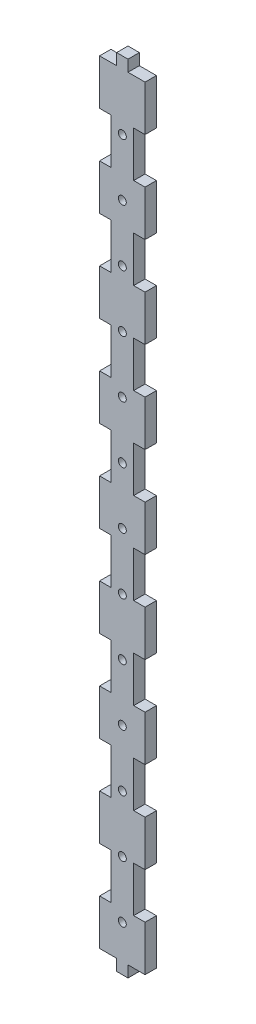
SolidWorks part; units mm, degrees
ref_plane "Front Plane" through (0, 0, 0) normal (0, 0, 1) x (1, 0, 0)
ref_plane "Top Plane" through (0, 0, 0) normal (0, 1, 0) x (1, 0, 0)
ref_plane "Right Plane" through (0, 0, 0) normal (1, 0, 0) x (0, 0, -1)
sketch "Model" plane through (0, 0, 0) normal (0, 0, 1) x (1, 0, 0)
  line L0 (5, -152.5) -> (0, -152.5)
  line L1 (5, -172.5) -> (5, -152.5)
  line L2 (-2.5, -172.5) -> (5, -172.5)
  line L3 (-2.5, -177.5) -> (-2.5, -172.5)
  line L4 (-7.5, -177.5) -> (-2.5, -177.5)
  line L5 (-7.5, -172.5) -> (-7.5, -177.5)
  line L6 (-15, -172.5) -> (-7.5, -172.5)
  line L7 (-15, -152.5) -> (-15, -172.5)
  line L8 (-10, -152.5) -> (-15, -152.5)
  line L9 (-10, -132.5) -> (-10, -152.5)
  line L10 (-15, -132.5) -> (-10, -132.5)
  line L11 (-15, -112.5) -> (-15, -132.5)
  line L12 (-10, -112.5) -> (-15, -112.5)
  line L13 (-10, -92.5) -> (-10, -112.5)
  line L14 (-15, -92.5) -> (-10, -92.5)
  line L15 (-15, -72.5) -> (-15, -92.5)
  line L16 (-10, -72.5) -> (-15, -72.5)
  line L17 (-10, -52.5) -> (-10, -72.5)
  line L18 (-15, -52.5) -> (-10, -52.5)
  line L19 (-15, -32.5) -> (-15, -52.5)
  line L20 (-10, -32.5) -> (-15, -32.5)
  line L21 (-10, -12.5) -> (-10, -32.5)
  line L22 (-15, -12.5) -> (-10, -12.5)
  line L23 (-15, 7.5) -> (-15, -12.5)
  line L24 (-10, 7.5) -> (-15, 7.5)
  line L25 (-10, 27.5) -> (-10, 7.5)
  line L26 (-15, 27.5) -> (-10, 27.5)
  line L27 (-15, 47.5) -> (-15, 27.5)
  line L28 (-10, 47.5) -> (-15, 47.5)
  line L29 (-10, 67.5) -> (-10, 47.5)
  line L30 (-15, 67.5) -> (-10, 67.5)
  line L31 (-15, 87.5) -> (-15, 67.5)
  line L32 (-10, 87.5) -> (-15, 87.5)
  line L33 (-10, 107.5) -> (-10, 87.5)
  line L34 (-15, 107.5) -> (-10, 107.5)
  line L35 (-15, 127.5) -> (-15, 107.5)
  line L36 (-10, 127.5) -> (-15, 127.5)
  line L37 (-10, 147.5) -> (-10, 127.5)
  line L38 (-15, 147.5) -> (-10, 147.5)
  line L39 (-15, 167.5) -> (-15, 147.5)
  line L40 (-7.5, 167.5) -> (-15, 167.5)
  line L41 (-7.5, 172.5) -> (-7.5, 167.5)
  line L42 (-2.5, 172.5) -> (-7.5, 172.5)
  line L43 (-2.5, 167.5) -> (-2.5, 172.5)
  line L44 (5, 167.5) -> (-2.5, 167.5)
  line L45 (5, 147.5) -> (5, 167.5)
  line L46 (0, 147.5) -> (5, 147.5)
  line L47 (0, 127.5) -> (0, 147.5)
  line L48 (5, 127.5) -> (0, 127.5)
  line L49 (5, 107.5) -> (5, 127.5)
  line L50 (0, 107.5) -> (5, 107.5)
  line L51 (0, 87.5) -> (0, 107.5)
  line L52 (5, 87.5) -> (0, 87.5)
  line L53 (5, 67.5) -> (5, 87.5)
  line L54 (0, 67.5) -> (5, 67.5)
  line L55 (0, 47.5) -> (0, 67.5)
  line L56 (5, 47.5) -> (0, 47.5)
  line L57 (5, 27.5) -> (5, 47.5)
  line L58 (0, 27.5) -> (5, 27.5)
  line L59 (0, 7.5) -> (0, 27.5)
  line L60 (5, 7.5) -> (0, 7.5)
  line L61 (5, -12.5) -> (5, 7.5)
  line L62 (0, -12.5) -> (5, -12.5)
  line L63 (0, -32.5) -> (0, -12.5)
  line L64 (5, -32.5) -> (0, -32.5)
  line L65 (5, -52.5) -> (5, -32.5)
  line L66 (0, -52.5) -> (5, -52.5)
  line L67 (0, -72.5) -> (0, -52.5)
  line L68 (5, -72.5) -> (0, -72.5)
  line L69 (5, -92.5) -> (5, -72.5)
  line L70 (0, -92.5) -> (5, -92.5)
  line L71 (0, -112.5) -> (0, -92.5)
  line L72 (5, -112.5) -> (0, -112.5)
  line L73 (5, -132.5) -> (5, -112.5)
  line L74 (0, -132.5) -> (5, -132.5)
  line L75 (0, -152.5) -> (0, -132.5)
  circle A0 centre (-5, 142.5) radius 1.75
  circle A1 centre (-5, 117.5) radius 1.75
  circle A2 centre (-5, 92.5) radius 1.75
  circle A3 centre (-5, 67.5) radius 1.75
  circle A4 centre (-5, 42.5) radius 1.75
  circle A5 centre (-5, 17.5) radius 1.75
  circle A6 centre (-5, -7.5) radius 1.75
  circle A7 centre (-5, -32.5) radius 1.75
  circle A8 centre (-5, -57.5) radius 1.75
  circle A9 centre (-5, -82.5) radius 1.75
  circle A10 centre (-5, -107.5) radius 1.75
  circle A11 centre (-5, -132.5) radius 1.75
  circle A12 centre (-5, -157.5) radius 1.75
extrude "Boss-Extrude1" add sketch "Model" along normal blind 5
